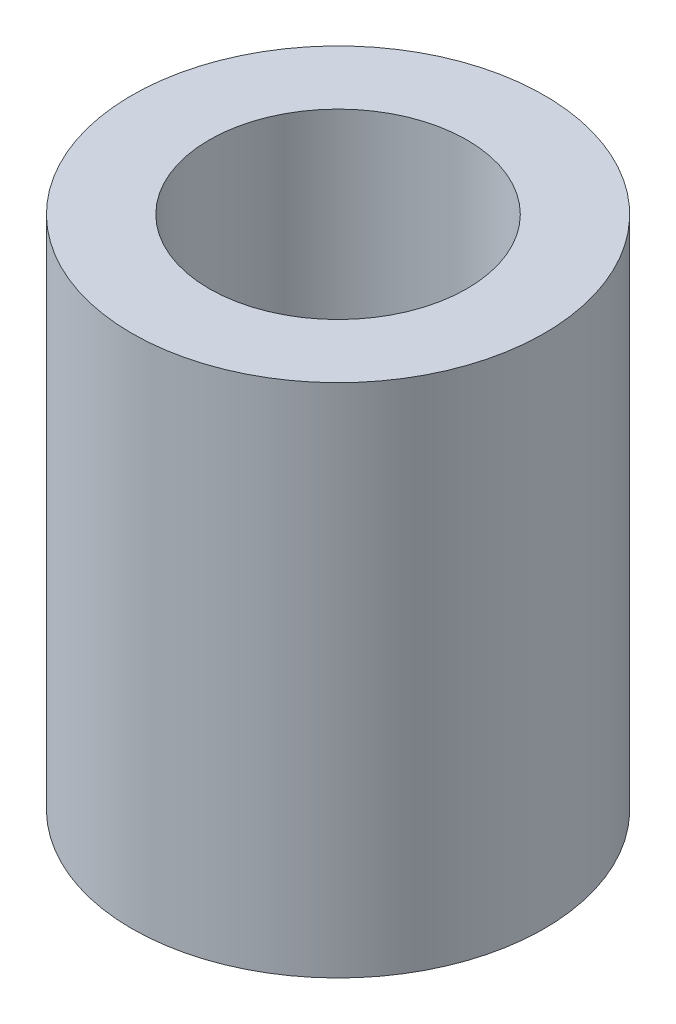
SolidWorks part; units mm, degrees
ref_plane "Front" through (0, 0, 0) normal (0, 0, 1) x (1, 0, 0)
ref_plane "Top" through (0, 0, 0) normal (0, 1, 0) x (1, 0, 0)
ref_plane "Right" through (0, 0, 0) normal (1, 0, 0) x (0, 0, -1)
sketch "Sketch1" plane through (0, 0, 0) normal (0, 1, 0) x (1, 0, 0)
  circle A0 centre (0, 0) radius 5
  circle A1 centre (0, 0) radius 8
  dimension "D1" = 10
  dimension "D2" = 3
extrude "Boss-Extrude1" add sketch "Sketch1" along normal blind 20
